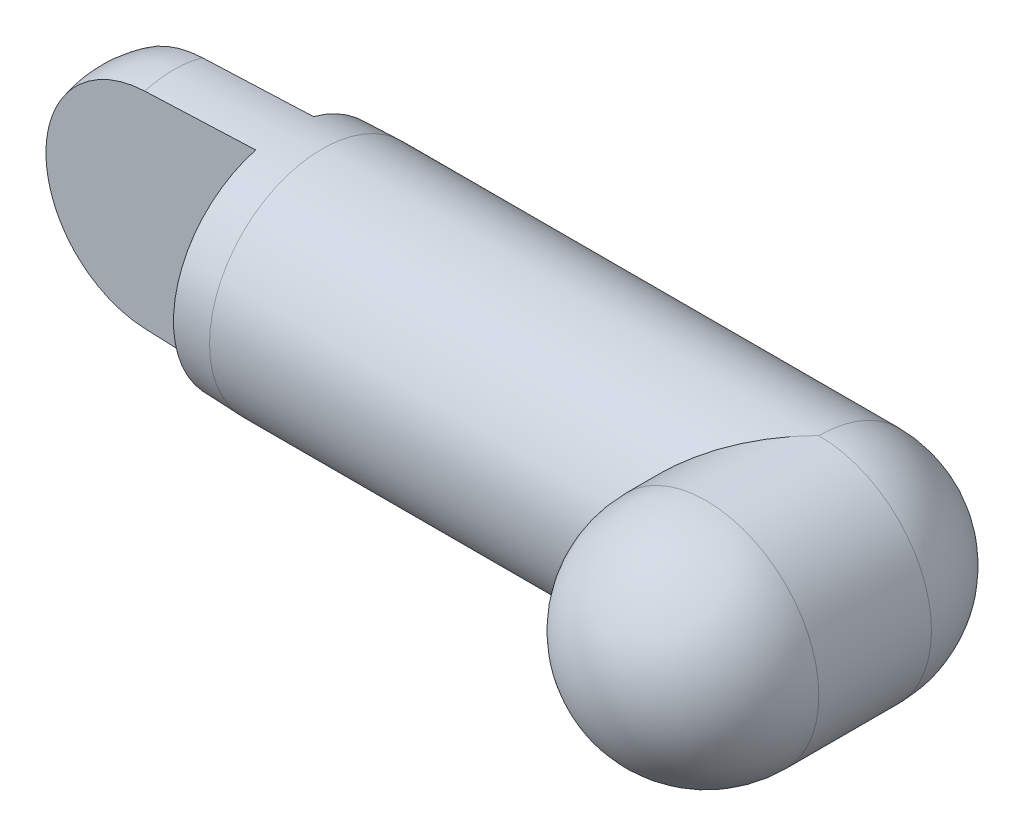
SolidWorks part; units mm, degrees
ref_plane "Front Plane" through (0, 0, 0) normal (0, 0, 1) x (1, 0, 0)
ref_plane "Top Plane" through (0, 0, 0) normal (0, 1, 0) x (1, 0, 0)
ref_plane "Right Plane" through (0, 0, 0) normal (1, 0, 0) x (0, 0, -1)
sketch "Sketch1" plane through (0, 0, 0) normal (0, 0, 1) x (1, 0, 0)
  line L0 (-1000, 0) -> (49000, 0) construction
  line L1 (-57.3511, 46.9535) -> (8, 49.53)
  line L2 (8, 49.53) -> (226.44, 49.53)
  line L3 (-102.49, 0) -> (275.97, 0)
  line L4 (8, -950.47) -> (8, 49049.53) construction
  arc A0 (-57.3511, 46.9535) -> (-102.49, 0) centre (-55.5, 0) ccw
  arc A1 (275.97, 0) -> (226.44, 49.53) centre (226.44, 0) ccw
  dimension "D3" = 93.98
  dimension "D4" = 99.06
  dimension "D1" = 281.94
  dimension "D2" = 55.5
  dimension "D5" = 63.5
  dimension "D6" = 49.53
revolve "Revolve1" add sketch "Sketch1" angle 360 about L0
sketch "Sketch2" plane through (0, 0, 0) normal (0, 1, 0) x (1, 0, 0)
  line L0 (-1000, 0) -> (49000, 0) construction
  line L1 (275.97, -989.901) -> (275.97, 49010.099) construction
  line L2 (-102.49, -88.9) -> (-8.51, -12.7) construction
  line L3 (-102.49, 88.9) -> (-8.51, 88.9)
  line L4 (-102.49, 88.9) -> (-102.49, 12.7)
  line L5 (-102.49, 12.7) -> (-8.51, 12.7)
  line L6 (-8.51, 88.9) -> (-8.51, 12.7)
  line L7 (-102.49, 88.9) -> (-8.51, 12.7) construction
  line L8 (-102.49, 12.7) -> (-8.51, 88.9) construction
  line L9 (-102.49, -12.7) -> (-8.51, -88.9) construction
  line L10 (-102.49, -12.7) -> (-8.51, -12.7)
  line L11 (275.97, 989.901) -> (275.97, -49010.099) construction
  line L12 (-8.51, -88.9) -> (-8.51, -12.7)
  line L13 (-102.49, -88.9) -> (-8.51, -88.9)
  line L14 (-102.49, -88.9) -> (-102.49, -12.7)
  line L15 (-102.49, -984.8125) -> (-102.49, 49015.1875) construction
  arc A0 (226.44, -49.53) -> (226.44, 49.53) centre (226.44, 0) ccw construction
  arc A1 (-57.3511, 46.9535) -> (-57.3511, -46.9535) centre (-55.5, 0) ccw construction
  point P8 (-55.5, 50.8)
  dimension "D1" = 12.7
  dimension "D2" = 76.2
  dimension "D3" = 93.98
extrude "Cut-Extrude1" cut sketch "Sketch2" against normal through all and the other way through all
sketch "Sketch13" plane through (0, 0, 0) normal (0, 0, 1) x (1, 0, 0)
  circle A0 centre (226.44, 0) radius 49.53
  arc A4 (226.44, -49.53) -> (226.44, 49.53) centre (226.44, 0) ccw construction
extrude "Boss-Extrude4" add sketch "Sketch13" along normal blind 49.53
sketch "Sketch14" plane through (0, 0, 49.53) normal (0, 0, 1) x (1, 0, 0)
  line L0 (176.91, 0) -> (275.97, 0)
  arc A0 (275.97, 0) -> (176.91, 0) centre (226.44, 0) ccw
  circle A3 centre (226.44, 0) radius 49.53 construction
revolve "Revolve4" add sketch "Sketch14" angle 360 about L0
sketch3d "3DSketch1"
  line L0 (-55.5, 0, -127) -> (-55.5, 0, 127)
  line L1 (226.44, 0, -127) -> (226.44, 0, 49.53)
  line L2 (-102.49, 0, 0) -> (275.97, 0, 0)
  line L3 (226.44, -63.5, 0) -> (226.44, 63.5, 0)
  arc A0 (226.44, -49.53, 0) -> (226.44, 49.53, 0) centre (226.44, 0, 0) ccw construction
  circle A1 centre (226.44, 0, 49.53) radius 49.53 construction
  arc A2 (-57.3511, -45.2034, 12.7) -> (-57.3511, 45.2034, 12.7) centre (-55.5, 0, 12.7) ccw construction
  point P10 (226.44, 0, 49.53)
  point P11 (0, 0, 0)
  point P12 (0, 0, 0)
  point P15 (226.44, 0, 99.06)
  point P16 (-55.5, 0, 0)
  point P20 (-55.5, 0, -32.5412)
  point P23 (226.44, 0, 0)
  dimension "D1" = 127
  dimension "D3" = 49.53
  dimension "D4" = 127
  dimension "D5" = 254
